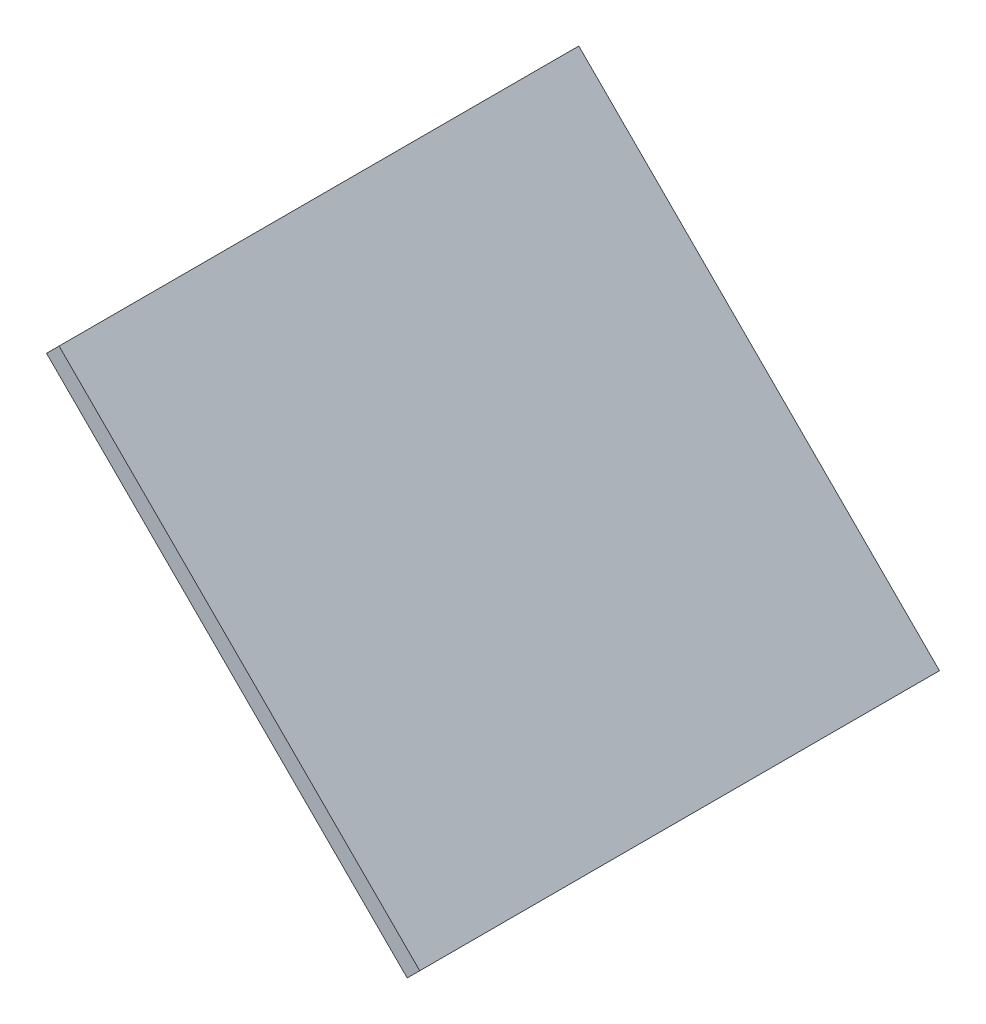
SolidWorks part; units mm, degrees
ref_plane "Front Plane" through (0, 0, 0) normal (0, 0, 1) x (1, 0, 0)
ref_plane "Top Plane" through (0, 0, 0) normal (0, 1, 0) x (1, 0, 0)
ref_plane "Right Plane" through (0, 0, 0) normal (1, 0, 0) x (0, 0, -1)
sketch "Sketch1" plane through (0, 0, 0) normal (0, 0, 1) x (1, 0, 0)
  line L0 (-126.8141, 1469.6159) -> (-514.6154, 1857.4172)
  line L1 (-514.6154, 1857.4172) -> (-528.0858, 1843.9468)
  line L2 (-528.0858, 1843.9468) -> (-525.2525, 1842.8053)
  line L3 (-126.8141, 1469.6159) -> (-140.2845, 1456.1455)
  line L23 (-140.2845, 1456.1455) -> (-528.0858, 1843.9468)
  dimension "D1" = 19.05
extrude "Boss-Extrude1" add sketch "Sketch1" along normal blind 558.8
